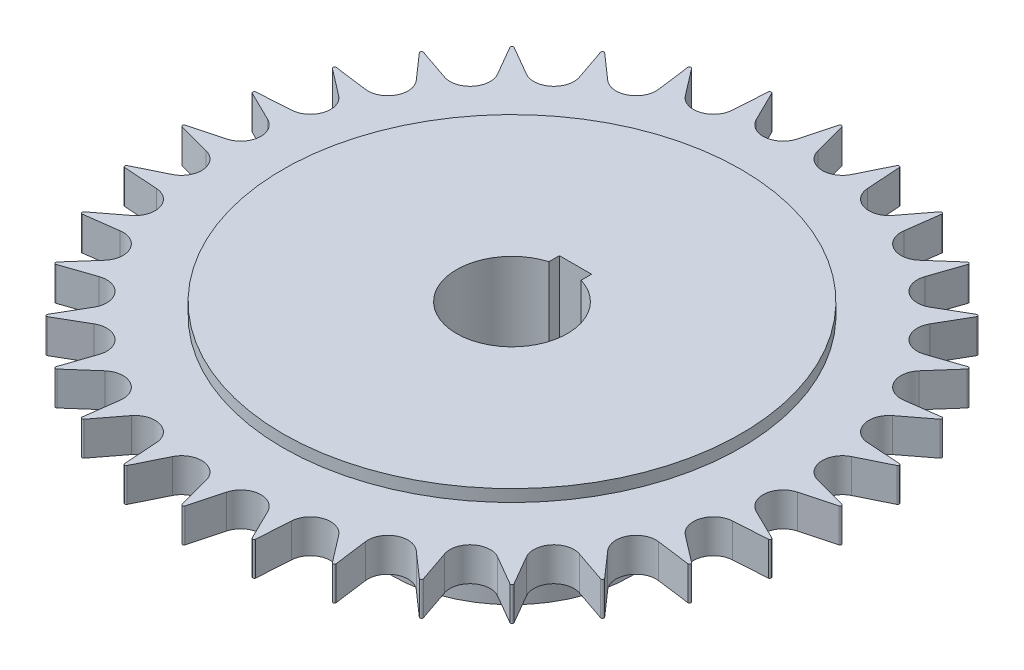
SolidWorks part; units mm, degrees
material "1079-2009-HR1"
ref_plane "Front Plane" through (0, 0, 0) normal (0, 0, 1) x (1, 0, 0)
ref_plane "Top Plane" through (0, 0, 0) normal (0, 1, 0) x (1, 0, 0)
ref_plane "Right Plane" through (0, 0, 0) normal (1, 0, 0) x (0, 0, -1)
sketch "Sketch1" plane through (0, 0, 0) normal (0, 1, 0) x (1, 0, 0)
  line L0 (0, 0) -> (39.9935, 201.061) construction
  line L1 (0, 0) -> (78.4501, 189.3953) construction
  line L2 (0, 0) -> (0, 205) construction
  line L3 (0, 0) -> (113.8919, 170.4513) construction
  line L4 (0, 0) -> (144.9569, 144.9569) construction
  line L5 (0, 0) -> (170.4513, 113.8919) construction
  line L6 (0, 0) -> (189.3953, 78.4501) construction
  line L7 (0, 0) -> (201.061, 39.9935) construction
  line L8 (0, 0) -> (205, 0) construction
  line L9 (0, 0) -> (201.061, -39.9935) construction
  line L10 (0, 0) -> (189.3953, -78.4501) construction
  line L11 (0, 0) -> (170.4513, -113.8919) construction
  line L12 (0, 0) -> (144.9569, -144.9569) construction
  line L13 (0, 0) -> (113.8919, -170.4513) construction
  line L14 (0, 0) -> (78.4501, -189.3953) construction
  line L15 (0, 0) -> (39.9935, -201.061) construction
  line L16 (0, 0) -> (0, -205) construction
  line L17 (0, 0) -> (-39.9935, -201.061) construction
  line L18 (0, 0) -> (-78.4501, -189.3953) construction
  line L19 (0, 0) -> (-113.8919, -170.4513) construction
  line L20 (0, 0) -> (-144.9569, -144.9569) construction
  line L21 (0, 0) -> (-170.4513, -113.8919) construction
  line L22 (0, 0) -> (-189.3953, -78.4501) construction
  line L23 (0, 0) -> (-201.061, -39.9935) construction
  line L24 (0, 0) -> (-205, 0) construction
  line L25 (0, 0) -> (-201.061, 39.9935) construction
  line L26 (0, 0) -> (-189.3953, 78.4501) construction
  line L27 (0, 0) -> (-170.4513, 113.8919) construction
  line L28 (0, 0) -> (-144.9569, 144.9569) construction
  line L29 (0, 0) -> (-113.8919, 170.4513) construction
  line L30 (0, 0) -> (-78.4501, 189.3953) construction
  line L31 (0, 0) -> (-39.9935, 201.061) construction
  line L32 (0, 0) -> (0, 205) construction
  line L33 (0, 0) -> (39.9935, 201.061) construction
  line L34 (0, 0) -> (-18.4316, 187.1395) construction
  line L35 (-6.3536, 183.9193) -> (-0.9219, 204.2917)
  line L36 (0, 0) -> (18.4316, 187.1395) construction
  line L37 (0.9219, 204.2917) -> (6.3536, 183.9193)
  line L38 (29.6494, 181.6248) -> (38.9512, 200.5462)
  line L39 (40.7595, 200.1865) -> (42.1123, 179.1458)
  line L40 (64.5129, 172.3506) -> (77.3274, 189.0937)
  line L41 (79.0307, 188.3882) -> (76.2528, 167.4878)
  line L42 (96.8973, 156.4531) -> (112.7319, 170.3745)
  line L43 (114.2649, 169.3502) -> (107.4629, 149.3934)
  line L44 (125.5579, 134.5432) -> (143.8042, 145.1079)
  line L45 (145.1079, 143.8042) -> (134.5432, 125.5579)
  line L46 (149.3934, 107.4629) -> (169.3502, 114.2649)
  line L47 (170.3745, 112.7319) -> (156.4531, 96.8973)
  line L48 (167.4878, 76.2528) -> (188.3882, 79.0307)
  line L49 (189.0937, 77.3274) -> (172.3506, 64.5129)
  line L50 (179.1458, 42.1123) -> (200.1865, 40.7595)
  line L51 (200.5462, 38.9512) -> (181.6248, 29.6494)
  line L52 (183.9193, 6.3536) -> (204.2917, 0.9219)
  line L53 (204.2917, -0.9219) -> (183.9193, -6.3536)
  line L54 (181.6248, -29.6494) -> (200.5462, -38.9512)
  line L55 (200.1865, -40.7595) -> (179.1458, -42.1123)
  line L56 (172.3506, -64.5129) -> (189.0937, -77.3274)
  line L57 (188.3882, -79.0307) -> (167.4878, -76.2528)
  line L58 (156.4531, -96.8973) -> (170.3745, -112.7319)
  line L59 (169.3502, -114.2649) -> (149.3934, -107.4629)
  line L60 (134.5432, -125.5579) -> (145.1079, -143.8042)
  line L61 (143.8042, -145.1079) -> (125.5579, -134.5432)
  line L62 (107.4629, -149.3934) -> (114.2649, -169.3502)
  line L63 (112.7319, -170.3745) -> (96.8973, -156.4531)
  line L64 (76.2528, -167.4878) -> (79.0307, -188.3882)
  line L65 (77.3274, -189.0937) -> (64.5129, -172.3506)
  line L66 (42.1123, -179.1458) -> (40.7595, -200.1865)
  line L67 (38.9512, -200.5462) -> (29.6494, -181.6248)
  line L68 (6.3536, -183.9193) -> (0.9219, -204.2917)
  line L69 (-0.9219, -204.2917) -> (-6.3536, -183.9193)
  line L70 (-29.6494, -181.6248) -> (-38.9512, -200.5462)
  line L71 (-40.7595, -200.1865) -> (-42.1123, -179.1458)
  line L72 (-64.5129, -172.3506) -> (-77.3274, -189.0937)
  line L73 (-79.0307, -188.3882) -> (-76.2528, -167.4878)
  line L74 (-96.8973, -156.4531) -> (-112.7319, -170.3745)
  line L75 (-114.2649, -169.3502) -> (-107.4629, -149.3934)
  line L76 (-125.5579, -134.5432) -> (-143.8042, -145.1079)
  line L77 (-145.1079, -143.8042) -> (-134.5432, -125.5579)
  line L78 (-149.3934, -107.4629) -> (-169.3502, -114.2649)
  line L79 (-170.3745, -112.7319) -> (-156.4531, -96.8973)
  line L80 (-167.4878, -76.2528) -> (-188.3882, -79.0307)
  line L81 (-189.0937, -77.3274) -> (-172.3506, -64.5129)
  line L82 (-179.1458, -42.1123) -> (-200.1865, -40.7595)
  line L83 (-200.5462, -38.9512) -> (-181.6248, -29.6494)
  line L84 (-183.9193, -6.3536) -> (-204.2917, -0.9219)
  line L85 (-204.2917, 0.9219) -> (-183.9193, 6.3536)
  line L86 (-181.6248, 29.6494) -> (-200.5462, 38.9512)
  line L87 (-200.1865, 40.7595) -> (-179.1458, 42.1123)
  line L88 (-172.3506, 64.5129) -> (-189.0937, 77.3274)
  line L89 (-188.3882, 79.0307) -> (-167.4878, 76.2528)
  line L90 (-156.4531, 96.8973) -> (-170.3745, 112.7319)
  line L91 (-169.3502, 114.2649) -> (-149.3934, 107.4629)
  line L92 (-134.5432, 125.5579) -> (-145.1079, 143.8042)
  line L93 (-143.8042, 145.1079) -> (-125.5579, 134.5432)
  line L94 (-107.4629, 149.3934) -> (-114.2649, 169.3502)
  line L95 (-112.7319, 170.3745) -> (-96.8973, 156.4531)
  line L96 (-76.2528, 167.4878) -> (-79.0307, 188.3882)
  line L97 (-77.3274, 189.0937) -> (-64.5129, 172.3506)
  line L98 (-42.1123, 179.1458) -> (-40.7595, 200.1865)
  line L99 (-38.9512, 200.5462) -> (-29.6494, 181.6248)
  circle A0 centre (0, 0) radius 204.0459 construction
  circle A1 centre (0, 0) radius 205 construction
  arc A6 (0.9219, 204.2917) -> (-0.9219, 204.2917) centre (0, 204.0459) ccw
  arc A8 (-29.6494, 181.6248) -> (-6.3536, 183.9193) centre (-18.4316, 187.1395) ccw
  arc A9 (6.3536, 183.9193) -> (29.6494, 181.6248) centre (18.4316, 187.1395) ccw construction
  circle A10 centre (0, 204.0459) radius 0.9541 construction
  arc A11 (6.3536, 183.9193) -> (29.6494, 181.6248) centre (18.4316, 187.1395) ccw
  arc A12 (40.7595, 200.1865) -> (38.9512, 200.5462) centre (39.8074, 200.1253) ccw
  arc A13 (42.1123, 179.1458) -> (64.5129, 172.3506) centre (54.5866, 179.9478) ccw
  arc A14 (79.0307, 188.3882) -> (77.3274, 189.0937) centre (78.085, 188.5139) ccw
  arc A15 (76.2528, 167.4878) -> (96.8973, 156.4531) centre (88.6438, 165.8409) ccw
  arc A16 (114.2649, 169.3502) -> (112.7319, 170.3745) centre (113.3619, 169.658) ccw
  arc A17 (107.4629, 149.3934) -> (125.5579, 134.5432) centre (119.2945, 145.3608) ccw
  arc A18 (145.1079, 143.8042) -> (143.8042, 145.1079) centre (144.2823, 144.2823) ccw
  arc A19 (134.5432, 125.5579) -> (149.3934, 107.4629) centre (145.3608, 119.2945) ccw
  arc A20 (170.3745, 112.7319) -> (169.3502, 114.2649) centre (169.658, 113.3619) ccw
  arc A21 (156.4531, 96.8973) -> (167.4878, 76.2528) centre (165.8409, 88.6438) ccw
  arc A22 (189.0937, 77.3274) -> (188.3882, 79.0307) centre (188.5139, 78.085) ccw
  arc A23 (172.3506, 64.5129) -> (179.1458, 42.1123) centre (179.9478, 54.5866) ccw
  arc A24 (200.5462, 38.9512) -> (200.1865, 40.7595) centre (200.1253, 39.8074) ccw
  arc A25 (181.6248, 29.6494) -> (183.9193, 6.3536) centre (187.1395, 18.4316) ccw
  arc A26 (204.2917, -0.9219) -> (204.2917, 0.9219) centre (204.0459, 0) ccw
  arc A27 (183.9193, -6.3536) -> (181.6248, -29.6494) centre (187.1395, -18.4316) ccw
  arc A28 (200.1865, -40.7595) -> (200.5462, -38.9512) centre (200.1253, -39.8074) ccw
  arc A29 (179.1458, -42.1123) -> (172.3506, -64.5129) centre (179.9478, -54.5866) ccw
  arc A30 (188.3882, -79.0307) -> (189.0937, -77.3274) centre (188.5139, -78.085) ccw
  arc A31 (167.4878, -76.2528) -> (156.4531, -96.8973) centre (165.8409, -88.6438) ccw
  arc A32 (169.3502, -114.2649) -> (170.3745, -112.7319) centre (169.658, -113.3619) ccw
  arc A33 (149.3934, -107.4629) -> (134.5432, -125.5579) centre (145.3608, -119.2945) ccw
  arc A34 (143.8042, -145.1079) -> (145.1079, -143.8042) centre (144.2823, -144.2823) ccw
  arc A35 (125.5579, -134.5432) -> (107.4629, -149.3934) centre (119.2945, -145.3608) ccw
  arc A36 (112.7319, -170.3745) -> (114.2649, -169.3502) centre (113.3619, -169.658) ccw
  arc A37 (96.8973, -156.4531) -> (76.2528, -167.4878) centre (88.6438, -165.8409) ccw
  arc A38 (77.3274, -189.0937) -> (79.0307, -188.3882) centre (78.085, -188.5139) ccw
  arc A39 (64.5129, -172.3506) -> (42.1123, -179.1458) centre (54.5866, -179.9478) ccw
  arc A40 (38.9512, -200.5462) -> (40.7595, -200.1865) centre (39.8074, -200.1253) ccw
  arc A41 (29.6494, -181.6248) -> (6.3536, -183.9193) centre (18.4316, -187.1395) ccw
  arc A42 (-0.9219, -204.2917) -> (0.9219, -204.2917) centre (0, -204.0459) ccw
  arc A43 (-6.3536, -183.9193) -> (-29.6494, -181.6248) centre (-18.4316, -187.1395) ccw
  arc A44 (-40.7595, -200.1865) -> (-38.9512, -200.5462) centre (-39.8074, -200.1253) ccw
  arc A45 (-42.1123, -179.1458) -> (-64.5129, -172.3506) centre (-54.5866, -179.9478) ccw
  arc A46 (-79.0307, -188.3882) -> (-77.3274, -189.0937) centre (-78.085, -188.5139) ccw
  arc A47 (-76.2528, -167.4878) -> (-96.8973, -156.4531) centre (-88.6438, -165.8409) ccw
  arc A48 (-114.2649, -169.3502) -> (-112.7319, -170.3745) centre (-113.3619, -169.658) ccw
  arc A49 (-107.4629, -149.3934) -> (-125.5579, -134.5432) centre (-119.2945, -145.3608) ccw
  arc A50 (-145.1079, -143.8042) -> (-143.8042, -145.1079) centre (-144.2823, -144.2823) ccw
  arc A51 (-134.5432, -125.5579) -> (-149.3934, -107.4629) centre (-145.3608, -119.2945) ccw
  arc A52 (-170.3745, -112.7319) -> (-169.3502, -114.2649) centre (-169.658, -113.3619) ccw
  arc A53 (-156.4531, -96.8973) -> (-167.4878, -76.2528) centre (-165.8409, -88.6438) ccw
  arc A54 (-189.0937, -77.3274) -> (-188.3882, -79.0307) centre (-188.5139, -78.085) ccw
  arc A55 (-172.3506, -64.5129) -> (-179.1458, -42.1123) centre (-179.9478, -54.5866) ccw
  arc A56 (-200.5462, -38.9512) -> (-200.1865, -40.7595) centre (-200.1253, -39.8074) ccw
  arc A57 (-181.6248, -29.6494) -> (-183.9193, -6.3536) centre (-187.1395, -18.4316) ccw
  arc A58 (-204.2917, 0.9219) -> (-204.2917, -0.9219) centre (-204.0459, 0) ccw
  arc A59 (-183.9193, 6.3536) -> (-181.6248, 29.6494) centre (-187.1395, 18.4316) ccw
  arc A60 (-200.1865, 40.7595) -> (-200.5462, 38.9512) centre (-200.1253, 39.8074) ccw
  arc A61 (-179.1458, 42.1123) -> (-172.3506, 64.5129) centre (-179.9478, 54.5866) ccw
  arc A62 (-188.3882, 79.0307) -> (-189.0937, 77.3274) centre (-188.5139, 78.085) ccw
  arc A63 (-167.4878, 76.2528) -> (-156.4531, 96.8973) centre (-165.8409, 88.6438) ccw
  arc A64 (-169.3502, 114.2649) -> (-170.3745, 112.7319) centre (-169.658, 113.3619) ccw
  arc A65 (-149.3934, 107.4629) -> (-134.5432, 125.5579) centre (-145.3608, 119.2945) ccw
  arc A66 (-143.8042, 145.1079) -> (-145.1079, 143.8042) centre (-144.2823, 144.2823) ccw
  arc A67 (-125.5579, 134.5432) -> (-107.4629, 149.3934) centre (-119.2945, 145.3608) ccw
  arc A68 (-112.7319, 170.3745) -> (-114.2649, 169.3502) centre (-113.3619, 169.658) ccw
  arc A69 (-96.8973, 156.4531) -> (-76.2528, 167.4878) centre (-88.6438, 165.8409) ccw
  arc A70 (-77.3274, 189.0937) -> (-79.0307, 188.3882) centre (-78.085, 188.5139) ccw
  arc A71 (-64.5129, 172.3506) -> (-42.1123, 179.1458) centre (-54.5866, 179.9478) ccw
  arc A72 (-38.9512, 200.5462) -> (-40.7595, 200.1865) centre (-39.8074, 200.1253) ccw
  arc A74 (41.8433, 183.3305) -> (36.6858, 184.4318) centre (0, 0) ccw construction
  point P270 (0, 0)
  dimension "D1" = 410
  dimension "PCD" = 408.0919
  dimension "D5" = 25
  dimension "D7" = 25
  dimension "D2" = 32
  dimension "D3" = 11.25
  dimension "D6" = 5.625
  dimension "D8" = 5.625
  dimension "D9" = 32
extrude "Boss-Extrude1" add sketch "Sketch1" along normal mid plane 21
sketch "Sketch2" plane through (0, 10.5, 0) normal (0, 1, 0) x (1, 0, 0)
  circle A0 centre (0, 0) radius 142.5
  dimension "D1" = 285
extrude "Boss-Extrude2" add sketch "Sketch2" along normal blind 7.5
mirror "Mirror1" about plane through (0, 0, 0) normal (0, 1, 0) of "Boss-Extrude2"
sketch "Sketch3" plane through (0, -18, 0) normal (0, -1, 0) x (1, 0, 0)
  circle A0 centre (0, 0) radius 74
  dimension "D1" = 148
extrude "Boss-Extrude3" add sketch "Sketch3" along normal blind 75
sketch "Sketch4" plane through (0, 18, 0) normal (0, 1, 0) x (1, 0, 0)
  line L1 (-10, 39.5) -> (10, 39.5)
  line L2 (-10, 39.5) -> (-10, 33.0189)
  line L4 (10, 39.5) -> (10, 33.0189)
  arc A0 (-10, 33.0189) -> (10, 33.0189) centre (0, 0) ccw
  point P3 (0, 34.5)
  point P4 (0, 39.5)
  dimension "D1" = 69
  dimension "D3" = 6.4811
  dimension "D2" = 20
extrude "Cut-Extrude1" cut sketch "Sketch4" against normal through all
